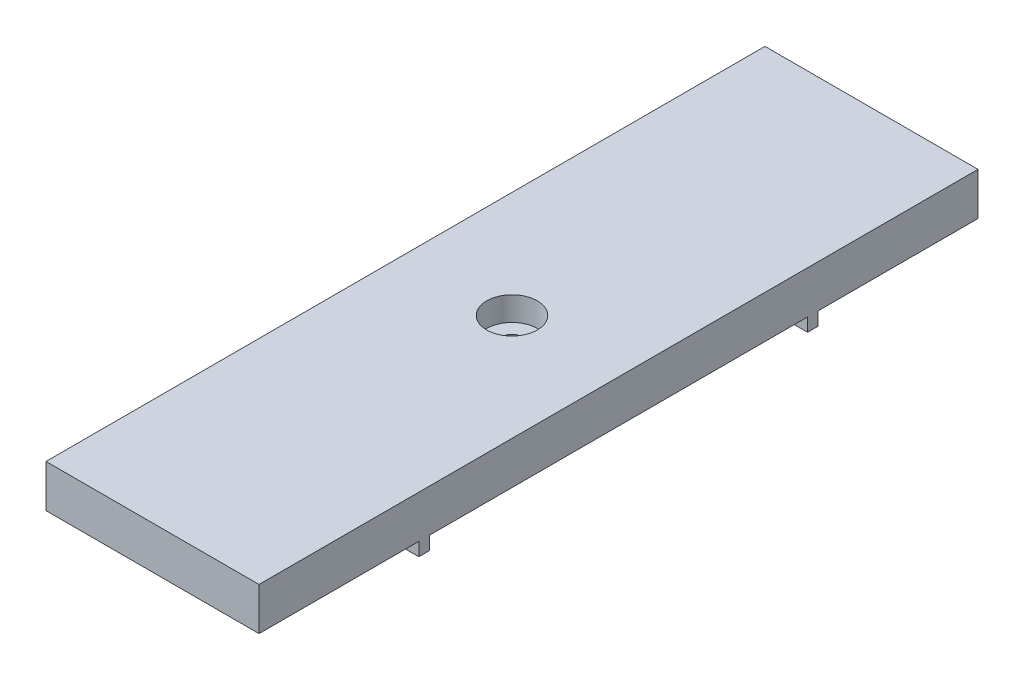
SolidWorks part; units mm, degrees
ref_plane "Front Plane" through (0, 0, 0) normal (0, 0, 1) x (1, 0, 0)
ref_plane "Top Plane" through (0, 0, 0) normal (0, 1, 0) x (1, 0, 0)
ref_plane "Right Plane" through (0, 0, 0) normal (1, 0, 0) x (0, 0, -1)
sketch "Sketch1" plane through (0, 0, 0) normal (0, 1, 0) x (1, 0, 0)
  circle A0 centre (0, 0) radius 3.85
  dimension "D1" = 7.7
extrude "Boss-Extrude1" add sketch "Sketch1" along normal blind 15
sketch "Sketch2" plane through (0, 15, 0) normal (0, 1, 0) x (1, 0, 0)
  line L1 (-20, -67.5) -> (20, -67.5)
  line L2 (-20, -67.5) -> (-20, 67.5)
  line L3 (-20, 67.5) -> (20, 67.5)
  line L4 (20, -67.5) -> (20, 67.5)
  point P4 (-20, 0)
  point P6 (0, 67.5)
  dimension "D1" = 40
  dimension "D2" = 135
extrude "Boss-Extrude3" add sketch "Sketch2" along normal blind 8
sketch "Sketch3" plane through (0, 15, 0) normal (0, -1, 0) x (1, 0, 0)
  line L0 (-20, -67.5) -> (-20, 67.5) construction
  line L1 (-20, -35.5) -> (20, -35.5)
  line L2 (-20, -35.5) -> (-20, -37.5)
  line L3 (-20, -37.5) -> (20, -37.5)
  line L4 (20, -35.5) -> (20, -37.5)
  line L5 (20, 67.5) -> (20, -67.5) construction
  line L6 (20, -67.5) -> (-20, -67.5) construction
  line L7 (-20, 0) -> (20, 0) construction
  line L8 (20, 35.5) -> (20, 37.5)
  line L9 (-20, 35.5) -> (-20, 37.5)
  line L10 (-20, 35.5) -> (20, 35.5)
  line L11 (-20, 37.5) -> (20, 37.5)
  dimension "D1" = 2
  dimension "D2" = 30
extrude "Boss-Extrude4" add sketch "Sketch3" along normal blind 2.5
sketch "Sketch4" plane through (0, 23, 0) normal (0, 1, 0) x (1, 0, 0)
  line L0 (0, -67.5) -> (0, 67.5) construction
  line L1 (-20, -67.5) -> (20, -67.5) construction
  line L2 (20, 67.5) -> (-20, 67.5) construction
  line L3 (-20, 0) -> (20, 0) construction
  line L4 (-20, 67.5) -> (-20, -67.5) construction
  line L5 (20, -67.5) -> (20, 67.5) construction
  circle A0 centre (0, 0) radius 3.85 construction
  circle A1 centre (0, 0) radius 4.75
  dimension "D1" = 7.7
  dimension "D2" = 9.5
extrude "Cut-Extrude1" cut sketch "Sketch4" against normal blind 4.5
sketch "Sketch5" plane through (0, 18.5, 0) normal (0, 1, 0) x (1, 0, 0)
  circle A0 centre (0, 0) radius 2
  dimension "D1" = 4
extrude "Cut-Extrude2" cut sketch "Sketch5" against normal blind 11
